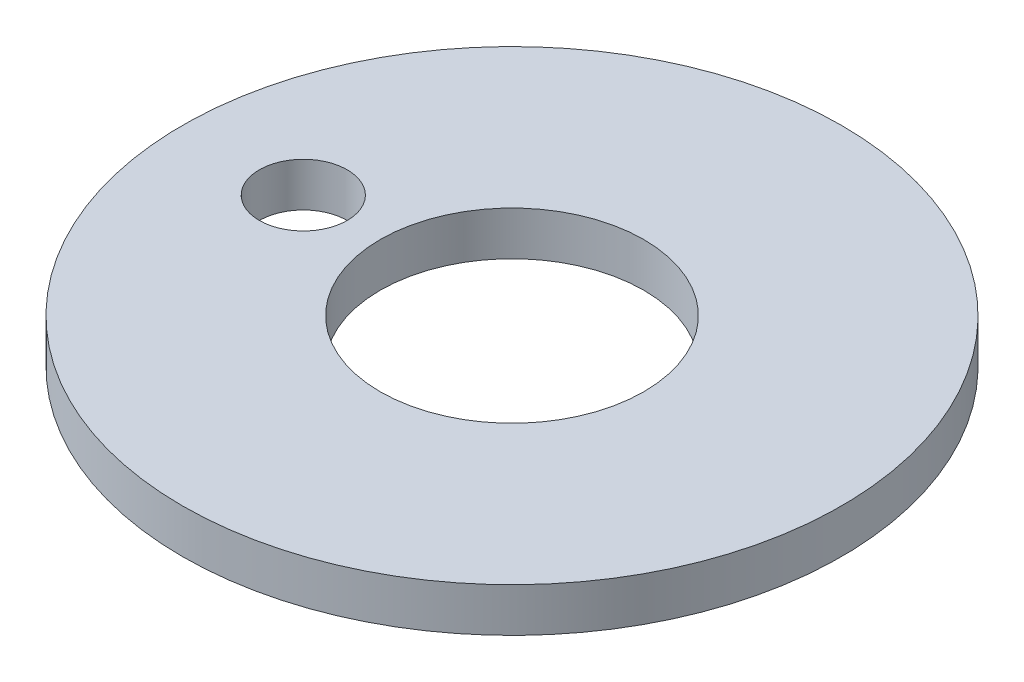
SolidWorks part; units mm, degrees
ref_plane "Front Plane" through (0, 0, 0) normal (0, 0, 1) x (1, 0, 0)
ref_plane "Top Plane" through (0, 0, 0) normal (0, 1, 0) x (1, 0, 0)
ref_plane "Right Plane" through (0, 0, 0) normal (1, 0, 0) x (0, 0, -1)
sketch "Sketch1" plane through (0, 0, 0) normal (0, 1, 0) x (1, 0, 0)
  line L0 (0, 0) -> (28.3599, 0) construction
  line L1 (0, 0) -> (0, 21.4021) construction
  circle A0 centre (0, 0) radius 15
  circle A1 centre (-9.5, 0) radius 2
  circle A3 centre (0, 0) radius 6
  dimension "D1" = 9.5
extrude "Boss-Extrude1" add sketch "Sketch1" along normal blind 2
